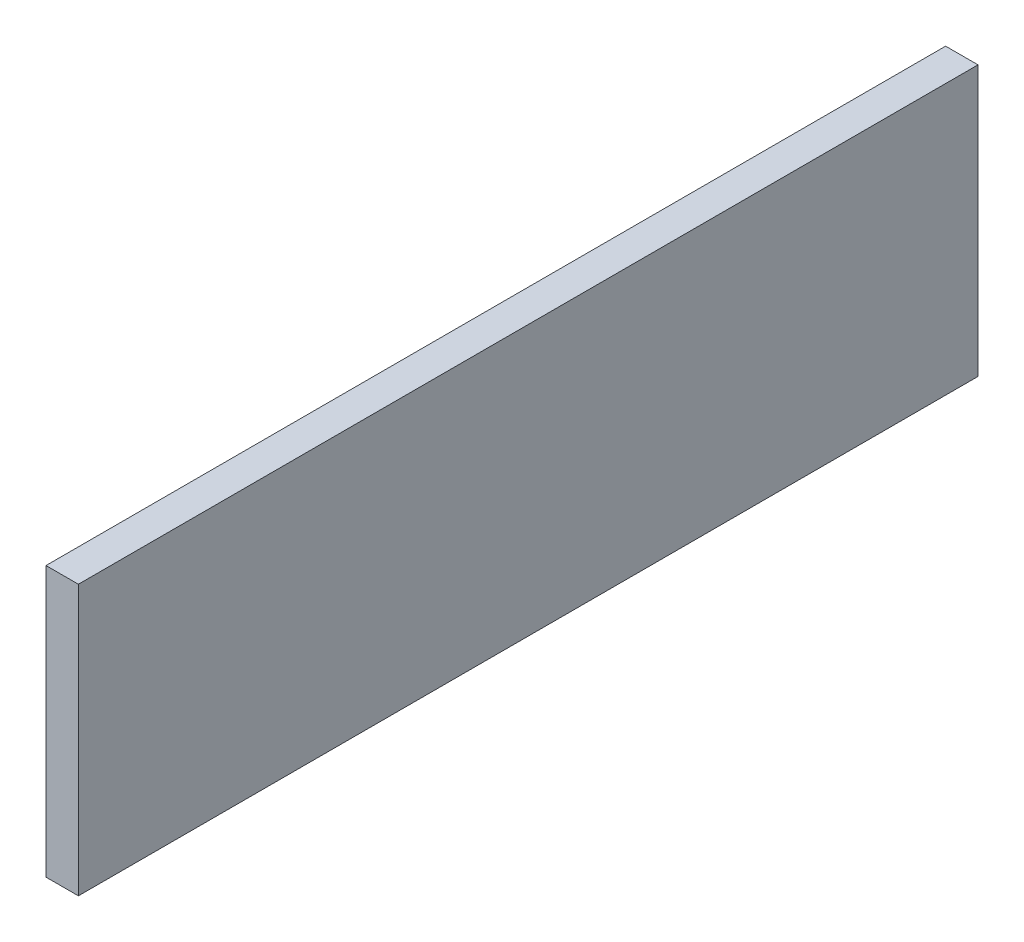
SolidWorks part; units mm, degrees
ref_plane "Front Plane" through (0, 0, 0) normal (0, 0, 1) x (1, 0, 0)
ref_plane "Top Plane" through (0, 0, 0) normal (0, 1, 0) x (1, 0, 0)
ref_plane "Right Plane" through (0, 0, 0) normal (1, 0, 0) x (0, 0, -1)
sketch "Sketch1" plane through (0, 0, 0) normal (1, 0, 0) x (0, 0, -1)
  line L1 (0, 0) -> (500, 0)
  line L2 (0, 0) -> (0, 150)
  line L3 (0, 150) -> (500, 150)
  line L4 (500, 0) -> (500, 150)
  dimension "D1" = 500
  dimension "D2" = 150
extrude "Boss-Extrude1" add sketch "Sketch1" along normal blind 18
